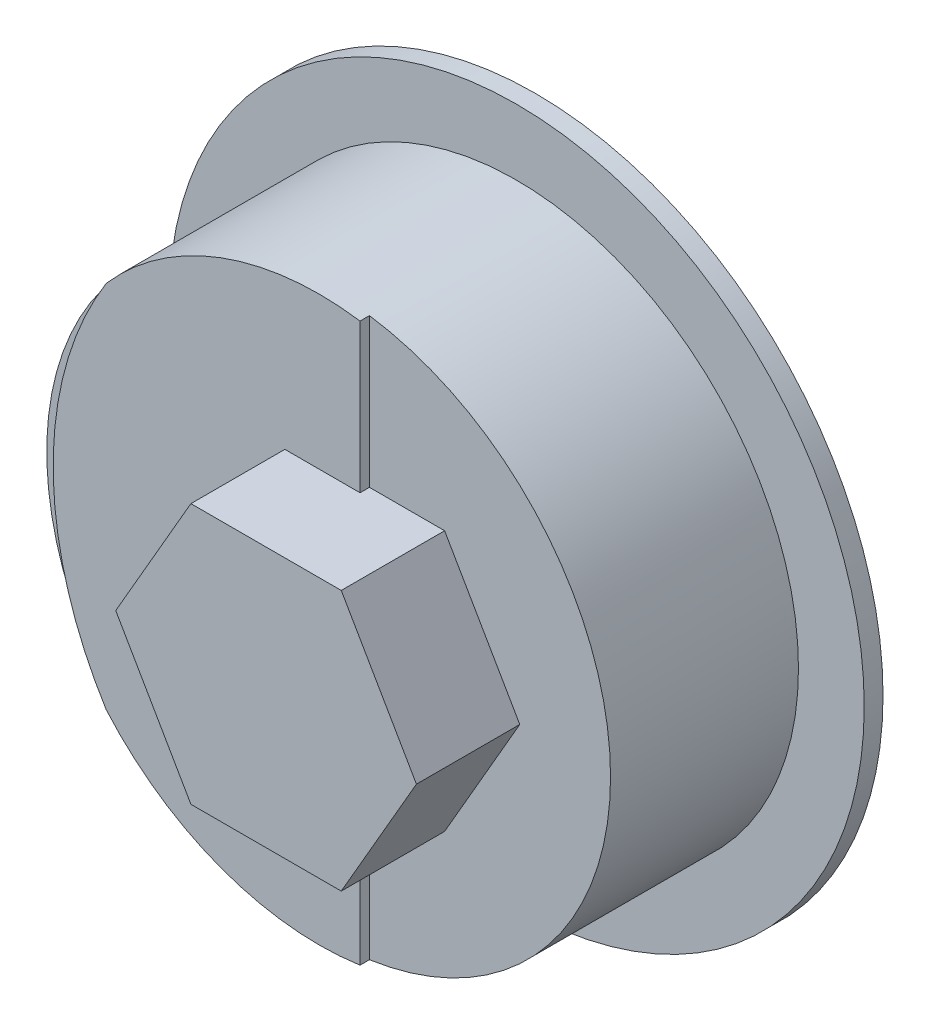
SolidWorks part; units mm, degrees
material "PETG"
ref_plane "Front Plane" through (0, 0, 0) normal (0, 0, 1) x (1, 0, 0)
ref_plane "Top Plane" through (0, 0, 0) normal (0, 1, 0) x (1, 0, 0)
ref_plane "Right Plane" through (0, 0, 0) normal (1, 0, 0) x (0, 0, -1)
sketch "Sketch1" plane through (0, 0, 0) normal (0, 0, 1) x (1, 0, 0)
  line L2 (-2, 3.4641) -> (-4, 0)
  line L3 (-4, 0) -> (-2, -3.4641)
  line L4 (-2, -3.4641) -> (2, -3.4641)
  line L5 (2, -3.4641) -> (4, 0)
  line L6 (4, 0) -> (2, 3.4641)
  line L7 (2, 3.4641) -> (-2, 3.4641)
  circle A0 centre (0, 0) radius 4 construction
  circle A1 centre (-2.17, 0) radius 15
  circle A2 centre (0, 0) radius 3.4641 construction
  dimension "D1" = 30
  dimension "D2" = 8
  dimension "D3" = 2.17
extrude "Boss-Extrude1" add sketch "Sketch1" along normal mid plane 10
sketch "Sketch3" plane through (0, 0, -5) normal (0, 0, -1) x (-1, 0, 0)
  circle A0 centre (2.17, 0) radius 18.5
  circle A1 centre (2.17, 0) radius 15 construction
  dimension "D1" = 37
extrude "Boss-Extrude3" add sketch "Sketch3" along normal blind 1
sketch "Sketch2" plane through (0, 0, -6) normal (0, 0, -1) x (-1, 0, 0)
  circle A0 centre (0, 0) radius 7.5
  dimension "D1" = 15
extrude "Boss-Extrude2" add sketch "Sketch2" along normal blind 0.5
sketch "Sketch4" plane through (0, 0, 5) normal (0, 0, 1) x (1, 0, 0)
  line L1 (4, 6.9282) -> (-4, 6.9282)
  line L2 (-4, 6.9282) -> (-8, 0)
  line L3 (-8, 0) -> (-4, -6.9282)
  line L4 (-4, -6.9282) -> (4, -6.9282)
  line L5 (4, -6.9282) -> (8, 0)
  line L6 (8, 0) -> (4, 6.9282)
  circle A0 centre (0, 0) radius 8 construction
  circle A1 centre (0, 0) radius 6.9282 construction
  dimension "D1" = 16
extrude "Boss-Extrude5" add sketch "Sketch4" along normal blind 5.5
sketch "Sketch5" plane through (0, 0, 5) normal (0, 0, 1) x (1, 0, 0)
  line L0 (-2.17, 17.9837) -> (-2.17, -17.9837) construction
  line L1 (-2.17, 0) -> (2.17, 0) construction
  line L2 (0, -18.3723) -> (0, 18.3723)
  circle A0 centre (2.17, 0) radius 18.5
  circle A1 centre (-2.17, 0) radius 15 construction
  circle A2 centre (-2.17, 0) radius 15 construction
  circle A3 centre (-2.17, 0) radius 18.5 construction
  point P9 (0, 0)
extrude "Boss-Extrude6" add sketch "Sketch5" along normal blind 0.5
equation "\"N\"= 21"
equation "\"R\"= 65mm"
equation "\"E\" = ROUND(\"R\" / \"N\" * 0.7, 2)"
equation "\"D3@Sketch1\"=\"E\""
